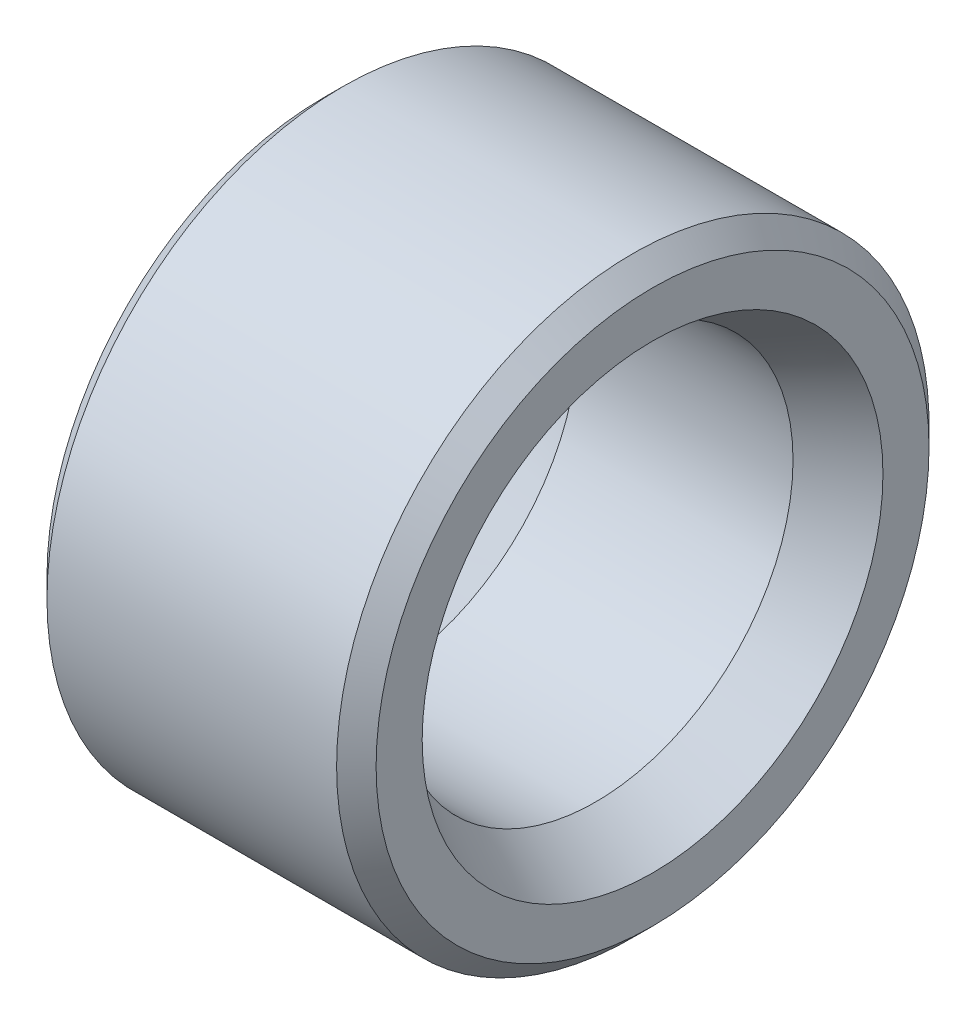
SolidWorks part; units mm, degrees
material "A2017"
ref_plane "Front Plane" through (0, 0, 0) normal (0, 0, 1) x (1, 0, 0)
ref_plane "Top Plane" through (0, 0, 0) normal (0, 1, 0) x (1, 0, 0)
ref_plane "Right Plane" through (0, 0, 0) normal (1, 0, 0) x (0, 0, -1)
sketch "Sketch1" plane through (0, 0, 0) normal (0, 0, 1) x (1, 0, 0)
  line L0 (0, 0) -> (5, 0) construction
  line L1 (0, 3) -> (0, 4.5)
  line L2 (0, 4.5) -> (5, 4.5)
  line L4 (5, 4.5) -> (5, 3)
  line L6 (5, 3) -> (0, 3)
  dimension "L" = 5
  dimension "D_s" = 6
  dimension "D" = 9
  dimension "T" = 1.5
revolve "Revolve1" add sketch "Sketch1" angle 360 about L0
chamfer "Chamfer1" distance 0.3 2 edges at (5, 0, 4.5) (0, 0, 4.5)
sketch "Sketch2" plane through (0, 0, 0) normal (0, 0, 1) x (1, 0, 0)
  line L0 (0, 0) -> (5, 0) construction
  line L1 (0, 3.5) -> (0, 3)
  line L2 (0, 3) -> (0.866, 3)
  line L3 (0.866, 3) -> (0, 3.5)
  line L4 (4.134, 3) -> (5, 3.5)
  line L5 (0, 3) -> (0, 4.5) construction
  line L8 (5, 3) -> (4.134, 3)
  line L9 (5, 3.5) -> (5, 3)
  line L10 (5, 3) -> (0, 3) construction
  line L11 (5, 4.5) -> (5, 3) construction
  dimension "FIX_4" = 0.5
  dimension "FIX_5" = 30
revolve "Cut-Revolve1" cut sketch "Sketch2" angle 360 about L0
